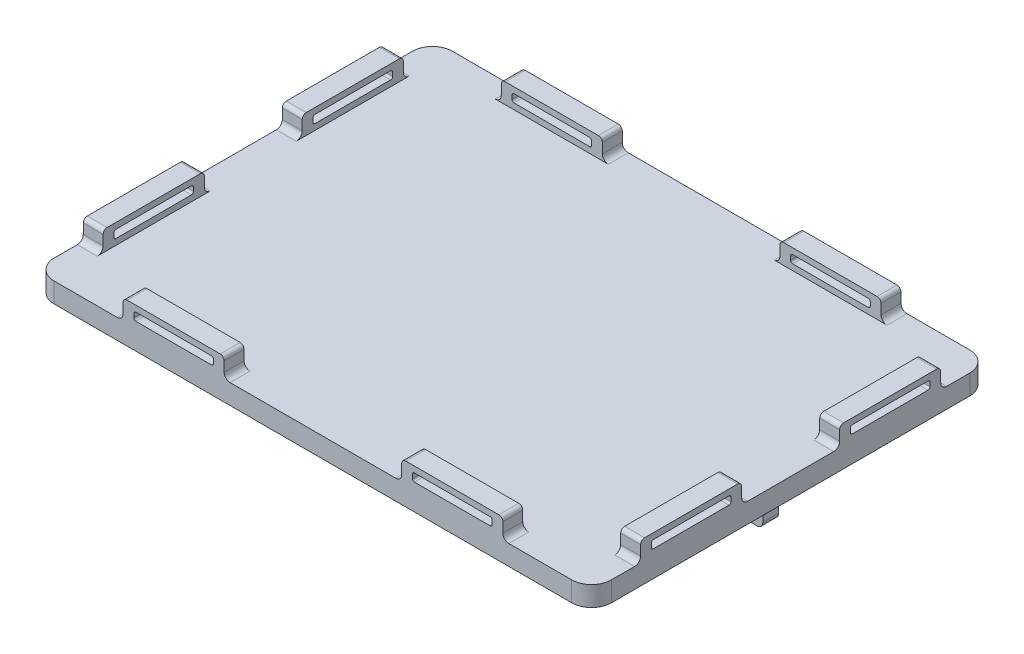
SolidWorks part; units mm, degrees
material "ABS"
ref_plane "Front Plane" through (0, 0, 0) normal (0, 0, 1) x (1, 0, 0)
ref_plane "Top Plane" through (0, 0, 0) normal (0, 1, 0) x (1, 0, 0)
ref_plane "Right Plane" through (0, 0, 0) normal (1, 0, 0) x (0, 0, -1)
sketch "Sketch1" plane through (0, 0, 0) normal (0, 1, 0) x (1, 0, 0)
  line L1 (5, 0) -> (135, 0)
  line L2 (0, 5) -> (0, 95)
  line L3 (5, 100) -> (135, 100)
  line L4 (140, 5) -> (140, 95)
  arc A0 (5, 0) -> (0, 5) centre (5, 5) cw
  arc A1 (135, 0) -> (140, 5) centre (135, 5) ccw
  arc A2 (135, 100) -> (140, 95) centre (135, 95) cw
  arc A3 (0, 95) -> (5, 100) centre (5, 95) cw
  point P7 (0, 0)
  point P10 (140, 0)
  point P13 (140, 100)
  dimension "D3" = 5
  dimension "D1" = 140
  dimension "D2" = 100
extrude "Boss-Extrude1" add sketch "Sketch1" along normal blind 5
sketch "Sketch2" plane through (0, 0, 0) normal (0, -1, 0) x (1, 0, 0)
  line L0 (5, 0) -> (135, 0) construction
  line L1 (12, -42) -> (16, -42)
  line L2 (12, -42) -> (12, -51)
  line L3 (12, -51) -> (16, -51)
  line L4 (16, -42) -> (16, -51)
  line L5 (119, -55) -> (128, -55)
  line L6 (119, -55) -> (119, -59)
  line L7 (119, -59) -> (128, -59)
  line L8 (128, -55) -> (128, -59)
  line L11 (0, -95) -> (0, -5) construction
  line L12 (140, -5) -> (140, -95) construction
  dimension "D1" = 9
  dimension "D2" = 4
  dimension "D3" = 9
  dimension "D4" = 4
  dimension "D5" = 12
  dimension "D6" = 12
  dimension "D7" = 42
  dimension "D8" = 55
extrude "Boss-Extrude2" add sketch "Sketch2" along normal blind 15
sketch "Sketch3" plane through (0, 5, 0) normal (0, 1, 0) x (1, 0, 0)
  line L10 (0, 95) -> (0, 5) construction
  line L11 (0, 87.7) -> (5, 87.7)
  line L12 (0, 87.7) -> (0, 62.3)
  line L23 (70, 100) -> (70, 0) construction
  line L24 (135, 100) -> (5, 100) construction
  line L25 (5, 0) -> (135, 0) construction
  line L26 (0, 62.3) -> (5, 62.3)
  line L27 (5, 87.7) -> (5, 62.3)
  line L28 (140, 5) -> (140, 95) construction
  line L29 (0, 37.7) -> (5, 37.7)
  line L30 (0, 37.7) -> (0, 12.3)
  line L31 (0, 12.3) -> (5, 12.3)
  line L32 (5, 37.7) -> (5, 12.3)
  line L33 (140, 87.7) -> (135, 87.7)
  line L34 (140, 87.7) -> (140, 62.3)
  line L35 (140, 62.3) -> (135, 62.3)
  line L36 (135, 87.7) -> (135, 62.3)
  line L37 (0, 50) -> (140, 50) construction
  line L38 (140, 37.7) -> (135, 37.7)
  line L39 (140, 37.7) -> (140, 12.3)
  line L40 (140, 12.3) -> (135, 12.3)
  line L41 (135, 37.7) -> (135, 12.3)
  line L43 (22.3, 100) -> (47.7, 100)
  line L44 (22.3, 100) -> (22.3, 95)
  line L45 (22.3, 95) -> (47.7, 95)
  line L46 (47.7, 100) -> (47.7, 95)
  line L47 (92.3, 100) -> (117.7, 100)
  line L48 (92.3, 100) -> (92.3, 95)
  line L49 (92.3, 95) -> (117.7, 95)
  line L50 (117.7, 100) -> (117.7, 95)
  line L51 (22.3, 0) -> (47.7, 0)
  line L52 (22.3, 0) -> (22.3, 5)
  line L53 (22.3, 5) -> (47.7, 5)
  line L54 (47.7, 0) -> (47.7, 5)
  line L55 (92.3, 0) -> (117.7, 0)
  line L56 (92.3, 0) -> (92.3, 5)
  line L57 (92.3, 5) -> (117.7, 5)
  line L58 (117.7, 0) -> (117.7, 5)
  dimension "D1" = 25.4
  dimension "D2" = 5
  dimension "D3" = 5
  dimension "D4" = 5
  dimension "D5" = 5
  dimension "D6" = 5
  dimension "D7" = 5
  dimension "D8" = 5
  dimension "D9" = 25.4
  dimension "D10" = 5
  dimension "D11" = 25.4
  dimension "D12" = 25.4
  dimension "D13" = 12.3
  dimension "D14" = 12.3
  dimension "D15" = 12.3
  dimension "D16" = 12.3
  dimension "D17" = 25.4
  dimension "D18" = 25.4
  dimension "D19" = 25.4
  dimension "D20" = 25.4
  dimension "D21" = 22.3
  dimension "D22" = 22.3
  dimension "D23" = 22.3
  dimension "D24" = 22.3
extrude "Boss-Extrude3" add sketch "Sketch3" along normal blind 5
sketch "Sketch4" plane through (0, 0, 0) normal (-1, 0, 0) x (0, 0, 1)
  line L0 (-87.7, 5) -> (-62.3, 5) construction
  line L1 (-87.7, 7.5) -> (-62.3, 7.5) construction
  line L2 (-84.5, 8.5) -> (-65.5, 8.5)
  line L3 (-85, 8) -> (-85, 7)
  line L4 (-84.5, 6.5) -> (-65.5, 6.5)
  line L5 (-65, 8) -> (-65, 7)
  line L6 (-87.7, 10) -> (-87.7, 5) construction
  line L7 (-62.3, 10) -> (-62.3, 5) construction
  line L8 (-85, 7.5) -> (-65, 7.5) construction
  line L9 (-75, 10) -> (-75, 5) construction
  line L10 (-87.7, 10) -> (-62.3, 10) construction
  line L11 (-75, 8.5) -> (-75, 6.5) construction
  line L12 (-37.7, 5) -> (-12.3, 5) construction
  line L13 (-35, 7.5) -> (-15, 7.5) construction
  line L14 (-34.5, 8.5) -> (-15.5, 8.5)
  line L15 (-35, 8) -> (-35, 7)
  line L16 (-34.5, 6.5) -> (-15.5, 6.5)
  line L17 (-15, 8) -> (-15, 7)
  line L18 (-25, 8.5) -> (-25, 6.5) construction
  line L19 (-37.7, 7.5) -> (-12.3, 7.5) construction
  line L20 (-37.7, 10) -> (-37.7, 5) construction
  line L21 (-12.3, 10) -> (-12.3, 5) construction
  line L22 (-25, 10) -> (-25, 5) construction
  line L23 (-37.7, 10) -> (-12.3, 10) construction
  arc A0 (-65.5, 8.5) -> (-65, 8) centre (-65.5, 8) cw
  arc A1 (-65.5, 6.5) -> (-65, 7) centre (-65.5, 7) ccw
  arc A2 (-85, 7) -> (-84.5, 6.5) centre (-84.5, 7) ccw
  arc A3 (-84.5, 8.5) -> (-85, 8) centre (-84.5, 8) ccw
  arc A4 (-15.5, 6.5) -> (-15, 7) centre (-15.5, 7) ccw
  arc A5 (-15.5, 8.5) -> (-15, 8) centre (-15.5, 8) cw
  arc A6 (-35, 7) -> (-34.5, 6.5) centre (-34.5, 7) ccw
  arc A7 (-34.5, 8.5) -> (-35, 8) centre (-34.5, 8) ccw
  point P22 (-75, 7.5)
  point P23 (-75, 7.5)
  point P26 (-65, 8.5)
  point P31 (-85, 6.5)
  point P34 (-85, 8.5)
  point P57 (-25, 7.5)
  point P58 (-25, 7.5)
  point P63 (-15, 8.5)
  point P66 (-35, 6.5)
  point P69 (-35, 8.5)
  dimension "D3" = 0.5
  dimension "D6" = 0.5
  dimension "D1" = 20
  dimension "D2" = 2
  dimension "D4" = 20
  dimension "D5" = 2
extrude "Cut-Extrude1" cut sketch "Sketch4" against normal through all
sketch "Sketch8" plane through (0, 0, 0) normal (0, 0, 1) x (1, 0, 0)
  line L0 (22.3, 5) -> (47.7, 5) construction
  line L1 (22.3, 7.5) -> (47.7, 7.5) construction
  line L2 (22.3, 10) -> (22.3, 5) construction
  line L3 (47.7, 10) -> (47.7, 5) construction
  line L4 (35, 10) -> (35, 5) construction
  line L5 (22.3, 10) -> (47.7, 10) construction
  line L6 (92.3, 5) -> (117.7, 5) construction
  line L7 (92.3, 7.5) -> (117.7, 7.5) construction
  line L8 (92.3, 10) -> (92.3, 5) construction
  line L9 (117.7, 10) -> (117.7, 5) construction
  line L10 (105, 10) -> (105, 5) construction
  line L11 (92.3, 10) -> (117.7, 10) construction
  line L12 (25, 7.5) -> (45, 7.5) construction
  line L13 (25.5, 8.5) -> (44.5, 8.5)
  line L14 (25, 8) -> (25, 7)
  line L15 (25.5, 6.5) -> (44.5, 6.5)
  line L16 (45, 8) -> (45, 7)
  line L17 (95.5, 8.5) -> (114.5, 8.5)
  line L18 (95, 8) -> (95, 7)
  line L19 (95.5, 6.5) -> (114.5, 6.5)
  line L20 (115, 8) -> (115, 7)
  line L21 (35, 8.5) -> (35, 6.5) construction
  line L22 (95, 7.5) -> (115, 7.5) construction
  line L23 (105, 8.5) -> (105, 6.5) construction
  arc A0 (114.5, 6.5) -> (115, 7) centre (114.5, 7) ccw
  arc A1 (114.5, 8.5) -> (115, 8) centre (114.5, 8) cw
  arc A2 (95, 7) -> (95.5, 6.5) centre (95.5, 7) ccw
  arc A3 (95.5, 8.5) -> (95, 8) centre (95.5, 8) ccw
  arc A4 (44.5, 6.5) -> (45, 7) centre (44.5, 7) ccw
  arc A5 (44.5, 8.5) -> (45, 8) centre (44.5, 8) cw
  arc A6 (25, 7) -> (25.5, 6.5) centre (25.5, 7) ccw
  arc A7 (25.5, 8.5) -> (25, 8) centre (25.5, 8) ccw
  point P40 (35, 7.5)
  point P41 (35, 7.5)
  point P46 (105, 7.5)
  point P47 (105, 7.5)
  point P50 (115, 6.5)
  point P53 (115, 8.5)
  point P58 (95, 8.5)
  point P63 (45, 8.5)
  point P66 (25, 6.5)
  point P69 (25, 8.5)
  dimension "D5" = 0.5
  dimension "D1" = 20
  dimension "D2" = 2
  dimension "D3" = 20
  dimension "D4" = 2
extrude "Cut-Extrude2" cut sketch "Sketch8" against normal through all
fillet "Fillet1" radius 1 16 edges at (137.5, 10, -87.7) (137.5, 10, -62.3) (2.5, 10, -62.3) (2.5, 10, -87.7) (22.3, 10, -97.5) (47.7, 10, -97.5) (137.5, 10, -37.7) (137.5, 10, -12.3) (2.5, 10, -37.7) (2.5, 10, -12.3) (117.7, 10, -97.5) (92.3, 10, -97.5) (117.7, 10, -2.5) (92.3, 10, -2.5) (47.7, 10, -2.5) (22.3, 10, -2.5)
fillet "Fillet2" radius 1.5 16 edges at (22.3, 5, -97.5) (47.7, 5, -97.5) (137.5, 5, -62.3) (137.5, 5, -87.7) (2.5, 5, -87.7) (2.5, 5, -62.3) (137.5, 5, -37.7) (137.5, 5, -12.3) (2.5, 5, -37.7) (2.5, 5, -12.3) (117.7, 5, -97.5) (92.3, 5, -97.5) (117.7, 5, -2.5) (92.3, 5, -2.5) (47.7, 5, -2.5) (22.3, 5, -2.5)
sketch "Sketch6" plane through (12, 0, 0) normal (-1, 0, 0) x (0, 0, 1)
  line L0 (-46.5, 0) -> (-46.5, -15) construction
  line L1 (-42, 0) -> (-51, 0) construction
  line L2 (-42, -15) -> (-51, -15) construction
  circle A1 centre (-46.5, -11) radius 1.55
  dimension "D1" = 3.1
  dimension "D2" = 4
extrude "Cut-Extrude3" cut sketch "Sketch6" against normal blind 5
sketch "Sketch7" plane through (0, 0, -55) normal (0, 0, 1) x (1, 0, 0)
  line L0 (123.5, 0) -> (123.5, -15) construction
  line L1 (128, 0) -> (119, 0) construction
  line L2 (128, -15) -> (119, -15) construction
  circle A1 centre (123.5, -11) radius 1.55
  dimension "D1" = 3.1
  dimension "D2" = 4
extrude "Cut-Extrude4" cut sketch "Sketch7" against normal blind 5
fillet "Fillet3" radius 1.5 4 edges at (128, -15, -57) (119, -15, -57) (14, -15, -42) (14, -15, -51)
fillet "Fillet4" radius 1.5 4 edges at (128, 0, -57) (119, 0, -57) (14, 0, -42) (14, 0, -51)
